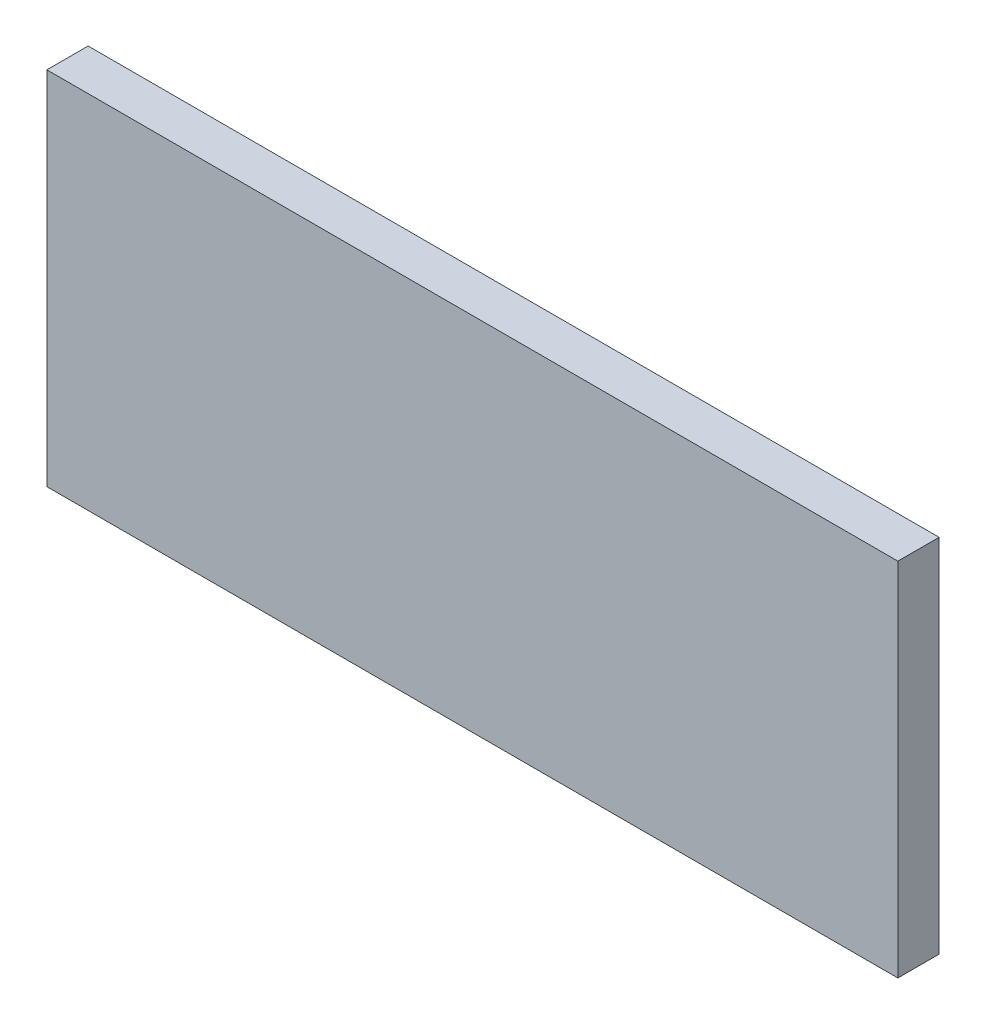
SolidWorks part; units mm, degrees
material "Q235A"
ref_plane "前视" through (0, 0, 0) normal (0, 0, 1) x (1, 0, 0)
ref_plane "上视" through (0, 0, 0) normal (0, 1, 0) x (1, 0, 0)
ref_plane "右视" through (0, 0, 0) normal (1, 0, 0) x (0, 0, -1)
sketch "草图1" plane through (0, 0, 0) normal (0, 0, 1) x (1, 0, 0)
  line L1 (165, -70) -> (-165, -70)
  line L2 (165, -70) -> (165, 70)
  line L3 (165, 70) -> (-165, 70)
  line L4 (-165, -70) -> (-165, 70)
  line L5 (165, -70) -> (-165, 70) construction
  line L6 (165, 70) -> (-165, -70) construction
  point P0 (0, 0)
  dimension "D1" = 140
  dimension "D2" = 330
extrude "凸台-拉伸1" add sketch "草图1" along normal blind 16
